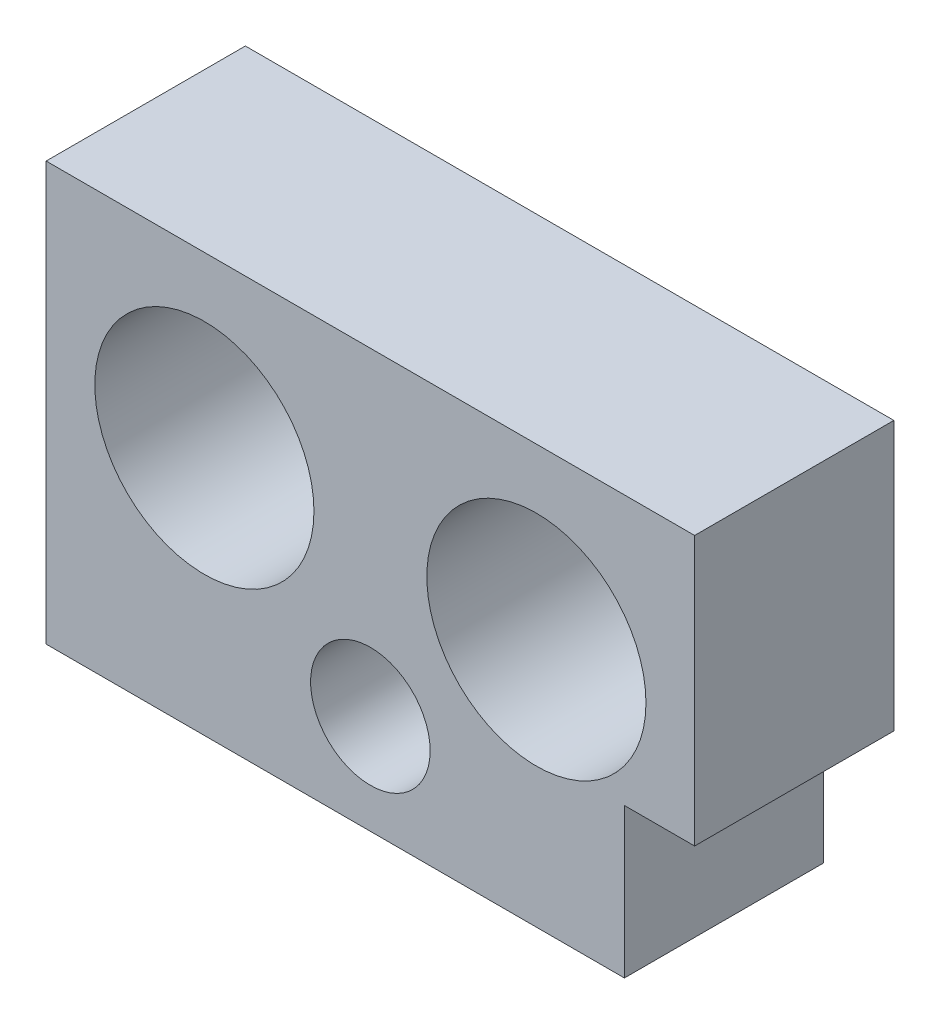
SolidWorks part; units mm, degrees
material "Manual Density from Real Component Plastica Fusoliera"
ref_plane "Piano frontale" through (0, 0, 0) normal (0, 0, 1) x (1, 0, 0)
ref_plane "Piano superiore" through (0, 0, 0) normal (0, 1, 0) x (1, 0, 0)
ref_plane "Piano destro" through (0, 0, 0) normal (1, 0, 0) x (0, 0, -1)
sketch "Schizzo1" plane through (0, 0, 0) normal (0, 0, 1) x (1, 0, 0)
  line L0 (-15.55, 0) -> (15.55, 0) construction
  line L2 (-30.55, 15) -> (30.55, 15) construction
  line L3 (-30.55, 15) -> (-30.55, -25) construction
  line L4 (-30.55, -25) -> (30.55, -25)
  line L5 (30.55, 15) -> (30.55, -25) construction
  line L6 (-30.55, -15) -> (30.55, -15) construction
  line L7 (-30.55, -25) -> (-32.55, -25)
  line L8 (-32.55, -25) -> (-32.55, 17)
  line L10 (32.55, 17) -> (32.55, -25)
  line L11 (32.55, -25) -> (30.55, -25)
  line L12 (-32.55, 17) -> (32.55, 17)
  circle A0 centre (-15.55, 0) radius 15 construction
  circle A1 centre (15.55, 0) radius 15 construction
  point P5 (0, 0)
  dimension "D2" = 30
  dimension "D1" = 31.1
  dimension "D3" = 10
  dimension "D4" = 2
  dimension "D5" = 2
  dimension "D6" = 2
extrude "ParallelepipedoBlocco" add sketch "Schizzo1" along normal blind 20
sketch "Schizzo2" plane through (0, 0, 20) normal (0, 0, 1) x (1, 0, 0)
  line L0 (-16.665, 0) -> (16.665, 0) construction
  line L1 (32.55, 17) -> (-32.55, 17) construction
  line L3 (-32.55, 15) -> (32.55, 15) construction
  line L4 (-32.55, 17) -> (-32.55, -25) construction
  line L5 (32.55, -25) -> (32.55, 17) construction
  circle A0 centre (-16.665, 0) radius 11
  circle A1 centre (16.665, 0) radius 11
  circle A2 centre (0, -15) radius 6
  point P4 (0, 0)
  dimension "D1" = 22
  dimension "D3" = 12
  dimension "D2" = 2
  dimension "D4" = 33.33
  dimension "D5" = 15
extrude "ForiTubiMotori" cut sketch "Schizzo2" against normal through all
ref_plane "PianoMedio" through (0, 0, 10) normal (0, 0, 1) x (1, 0, 0)
sketch "Schizzo3" plane through (0, 0, 20) normal (0, 0, 1) x (1, 0, 0)
  line L1 (32.55, -25) -> (25.5, -25)
  line L2 (32.55, -25) -> (32.55, -10)
  line L3 (32.55, -10) -> (25.5, -10)
  line L4 (25.5, -25) -> (25.5, -10)
  dimension "D1" = 15
  dimension "D2" = 7.05
extrude "SpazioMovimentoLevetta" cut sketch "Schizzo3" against normal through all
